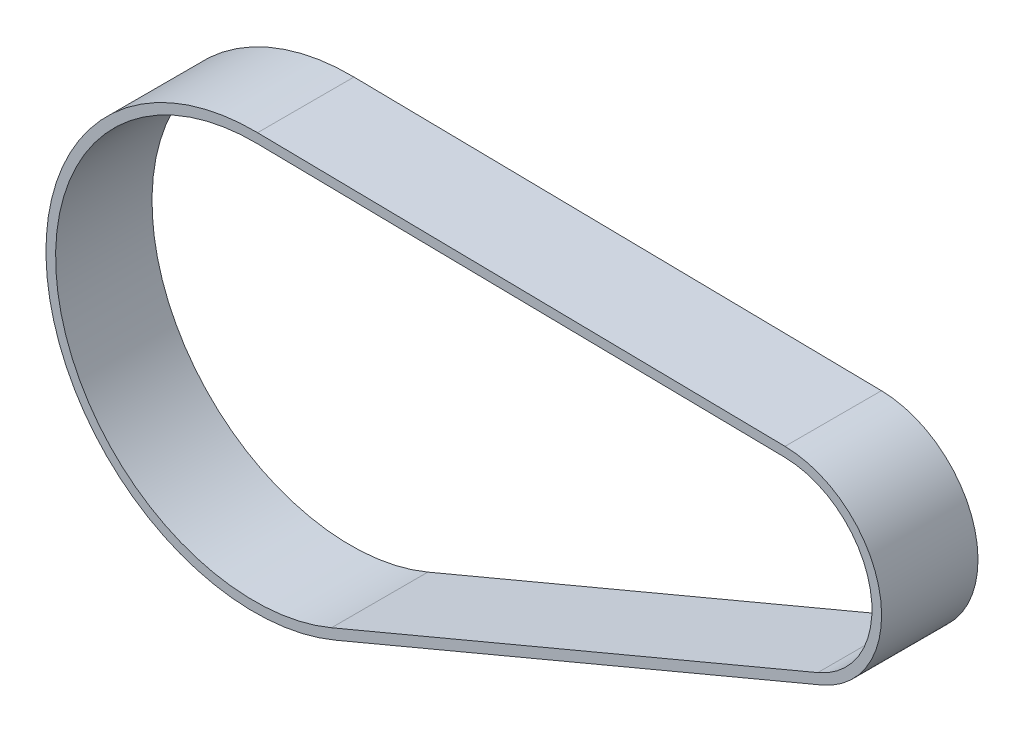
SolidWorks part; units mm, degrees
ref_plane "Front Plane" through (0, 0, 0) normal (0, 0, 1) x (1, 0, 0)
ref_plane "Top Plane" through (0, 0, 0) normal (0, 1, 0) x (1, 0, 0)
ref_plane "Right Plane" through (0, 0, 0) normal (1, 0, 0) x (0, 0, -1)
sketch "Sketch1" plane through (0, 0, 0) normal (0, 0, 1) x (1, 0, 0)
  line L0 (-25.87, 76.8365) -> (28.8376, 76.0156)
  line L1 (-18.1903, 37.199) -> (32.252, 58.3925)
  line L2 (-25.855, 77.8364) -> (28.8526, 77.0155)
  line L3 (-17.803, 36.2771) -> (32.6393, 57.4706)
  arc A0 (-25.87, 76.8365) -> (-18.1903, 37.199) centre (-26.1795, 56.2139) ccw
  arc A1 (32.252, 58.3925) -> (28.8376, 76.0156) centre (28.7, 66.8466) ccw
  arc A2 (32.6393, 57.4706) -> (28.8526, 77.0155) centre (28.7, 66.8466) ccw
  arc A3 (-25.855, 77.8364) -> (-17.803, 36.2771) centre (-26.1795, 56.2139) ccw
  point P8 (-22.1584, 41.5397)
  point P9 (-27.0076, 59.4023)
  point P10 (-27.0076, 59.4023)
  point P11 (-26.4764, 58.2338)
  point P12 (32.1189, 66.6739)
  dimension "D1" = 41.25
  dimension "D2" = 18.34
  dimension "D3" = 1
  dimension "D4" = 55.9
extrude "Boss-Extrude1" add sketch "Sketch1" along normal blind 10
